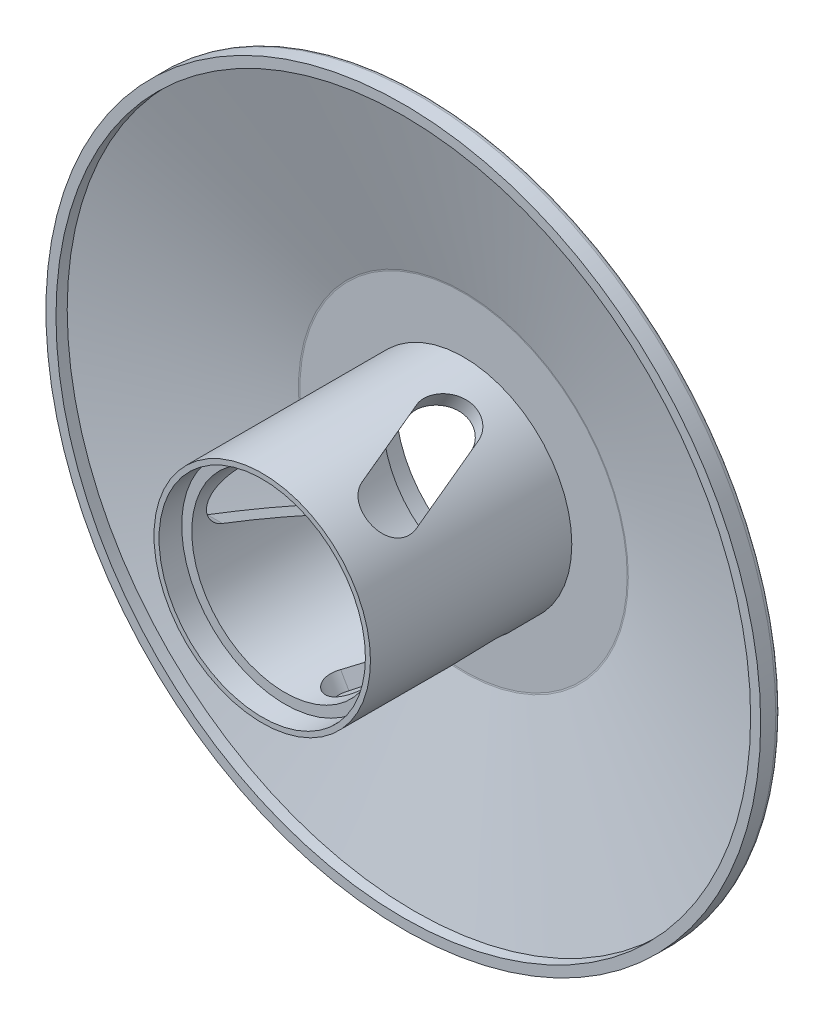
SolidWorks part; units mm, degrees
material "ASTM A36"
ref_plane "Plano frontal" through (0, 0, 0) normal (0, 0, 1) x (1, 0, 0)
ref_plane "Plano superior" through (0, 0, 0) normal (0, 1, 0) x (1, 0, 0)
ref_plane "Plano direito" through (0, 0, 0) normal (1, 0, 0) x (0, 0, -1)
sketch "Esboço1" plane through (0, 0, 0) normal (1, 0, 0) x (0, 0, -1)
  line L0 (-13.9775, 71) -> (-10.9775, 71)
  line L1 (-10.0116, 70.2588) -> (-0.1022, 33.2765)
  line L2 (0, 32.5) -> (0, 26.5)
  line L3 (5, 21.5) -> (5, 20.5)
  line L4 (0, 0) -> (42668.7999, 0) construction
  line L5 (5, 20.5) -> (0.5, 20.5)
  line L6 (0.5, 20.5) -> (0.5, 18.5)
  line L7 (0.5, 18.5) -> (-37.5, 18.5)
  line L8 (-37.5, 18.5) -> (-37.5, 20.5)
  line L9 (-37.5, 20.5) -> (-42, 20.5)
  line L10 (-13.9775, 69) -> (-11.7449, 69)
  line L11 (-11.7449, 69) -> (-2.0341, 32.7588)
  line L12 (-2, 32.5) -> (-2, 26.5)
  line L13 (-42, 20.5) -> (-42, 21.5)
  line L14 (-42, 21.5) -> (-2, 21.5)
  line L15 (-2, 21.5) -> (-2, 26.5)
  line L16 (-13.9775, 71) -> (-13.9775, 69)
  arc A0 (-10.9775, 71) -> (-10.0116, 70.2588) centre (-10.9775, 70) cw
  arc A1 (-0.1022, 33.2765) -> (0, 32.5) centre (-3, 32.5) cw
  arc A2 (0, 26.5) -> (0.5, 26) centre (0.5, 26.5) ccw
  arc A3 (0.5, 26) -> (5, 21.5) centre (0.5, 21.5) cw
  arc A4 (-11.7449, 69) -> (-11.7449, 69) centre (-11.7449, 69) cw
  arc A5 (-2.0341, 32.7588) -> (-2, 32.5) centre (-3, 32.5) cw
  dimension "D4" = 1
  dimension "D5" = 3
  dimension "D6" = 52
  dimension "D7" = 0.5
  dimension "D1" = 142
  dimension "D2" = 3
  dimension "D3" = 65
  dimension "D8" = 37
  dimension "D9" = 41
  dimension "D10" = 5
  dimension "D11" = 4.5
  dimension "D12" = 47
  dimension "D13" = 15
  dimension "D15" = 43
  dimension "D14" = 2
revolve "Revolução1" add sketch "Esboço1" angle 360 about L4
sketch "Esboço2" plane through (0, 0, 0) normal (1, 0, 0) x (0, 0, -1)
  line L0 (-12.8695, -3.0782) -> (-29.784, 3.0782) construction
  line L1 (-14.5796, -7.7766) -> (-31.4941, -1.6203)
  line L2 (-11.1594, 1.6203) -> (-28.0739, 7.7766)
  line L3 (-8.1711, -4.7883) -> (-34.4825, 4.7883) construction
  line L4 (-34.4825, 4.7883) -> (-42, 7.5244) construction
  line L6 (-42, 21.5) -> (-42, -21.5) construction
  line L7 (0, 0) -> (-21.3268, 0) construction
  arc A0 (-14.5796, -7.7766) -> (-11.1594, 1.6203) centre (-12.8695, -3.0782) ccw
  arc A1 (-28.0739, 7.7766) -> (-31.4941, -1.6203) centre (-29.784, 3.0782) ccw
  point P2 (-21.3268, 0)
  dimension "D1" = 8
  dimension "D2" = 36
  dimension "D3" = 10
  dimension "D4" = 20
extrude "Corte-extrusão1" cut sketch "Esboço2" against normal up to surface (21.4389 mm away)
pattern_circular "PadrãoCircular1" count 3 over 360 about axis through (0, 0, 0) along (0, 0, 1) of "Corte-extrusão1"
